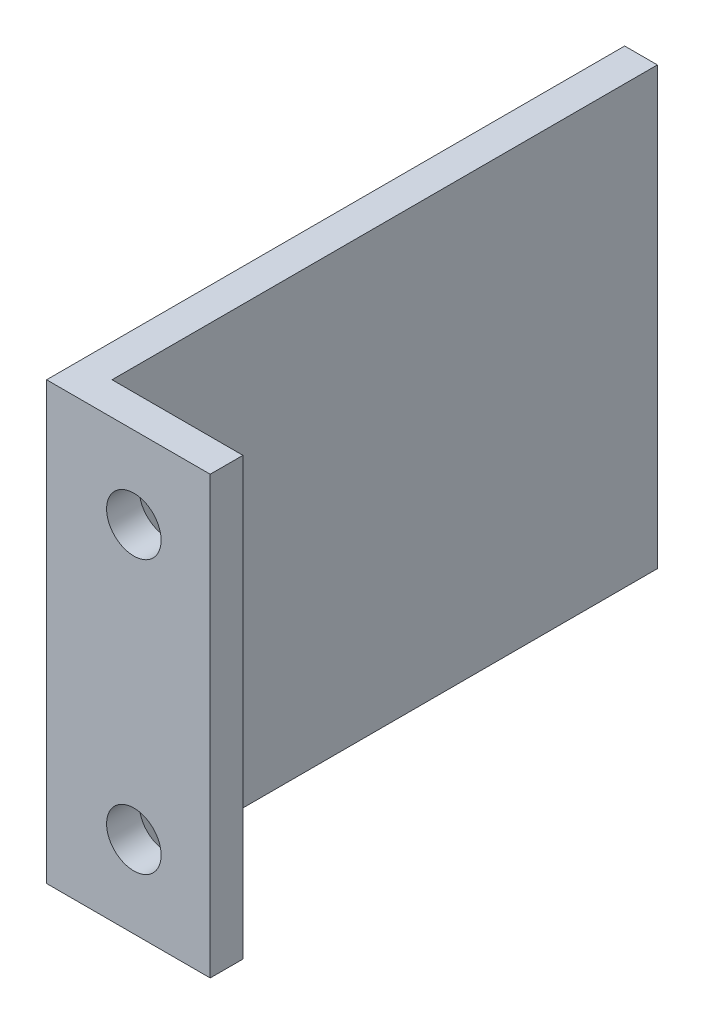
SolidWorks part; units mm, degrees
ref_plane "Front" through (0, 0, 0) normal (0, 0, 1) x (1, 0, 0)
ref_plane "Top" through (0, 0, 0) normal (0, 1, 0) x (1, 0, 0)
ref_plane "Right" through (0, 0, 0) normal (1, 0, 0) x (0, 0, -1)
sketch "Sketch1" plane through (0, 0, 0) normal (0, 0, 1) x (1, 0, 0)
  line L1 (-7.5, 20) -> (7.5, 20)
  line L2 (-7.5, 20) -> (-7.5, -20)
  line L3 (-7.5, -20) -> (7.5, -20)
  line L4 (7.5, 20) -> (7.5, -20)
  line L5 (-7.5, 20) -> (7.5, -20) construction
  line L6 (-7.5, -20) -> (7.5, 20) construction
  point P0 (0, 0)
  dimension "D1" = 40
  dimension "D2" = 15
extrude "Boss-Extrude1" add sketch "Sketch1" along normal blind 3
sketch "Sketch2" plane through (0, 0, 0) normal (0, 0, -1) x (-1, 0, 0)
  line L0 (-7.5, 20) -> (7.5, 20) construction
  line L1 (7.5, -20) -> (4.5, -20)
  line L2 (7.5, -20) -> (7.5, 20)
  line L3 (7.5, 20) -> (4.5, 20)
  line L4 (4.5, -20) -> (4.5, 20)
  dimension "D1" = 3
extrude "Boss-Extrude2" add sketch "Sketch2" along normal blind 50
sketch "Sketch3" plane through (0, 0, 3) normal (0, 0, 1) x (1, 0, 0)
  line L0 (7.5, 20) -> (-7.5, 20) construction
  line L1 (-7.5, 20) -> (-7.5, -20) construction
  circle A3 centre (0.5, 12.5) radius 2.5
  dimension "D1" = 5
  dimension "D2" = 7.5
  dimension "D3" = 8
extrude "Cut-Extrude1" cut sketch "Sketch3" against normal up to surface (3 mm away) up to face at (1.5, 0, 0)
pattern_linear "LPattern1" count 2 spacing 25 along (0, -1, 0) of "Cut-Extrude1"
